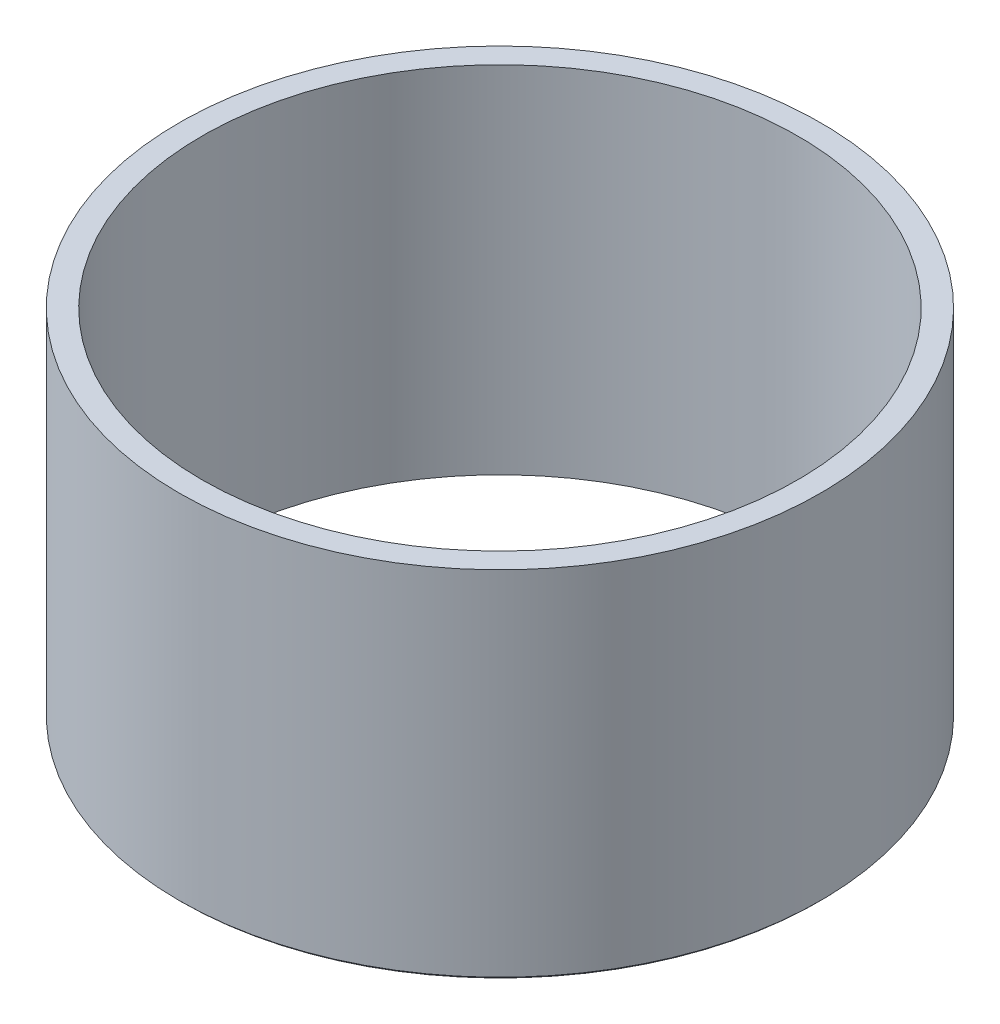
SolidWorks part; units mm, degrees
material "Aleación 1060"
ref_plane "Alzado" through (0, 0, 0) normal (0, 0, 1) x (1, 0, 0)
ref_plane "Planta" through (0, 0, 0) normal (0, 1, 0) x (1, 0, 0)
ref_plane "Vista lateral" through (0, 0, 0) normal (1, 0, 0) x (0, 0, -1)
sketch "Croquis1" plane through (0, 0, 0) normal (0, 1, 0) x (1, 0, 0)
  circle A0 centre (0, 0) radius 14
  circle A1 centre (0, 0) radius 13
  dimension "D1" = 28
  dimension "D2" = 1
extrude "Saliente-Extruir1" add sketch "Croquis1" along normal blind 15.5
chamfer "Chaflán1" distance 0.1 angle 45 1 edges at (0, 0, 14)
